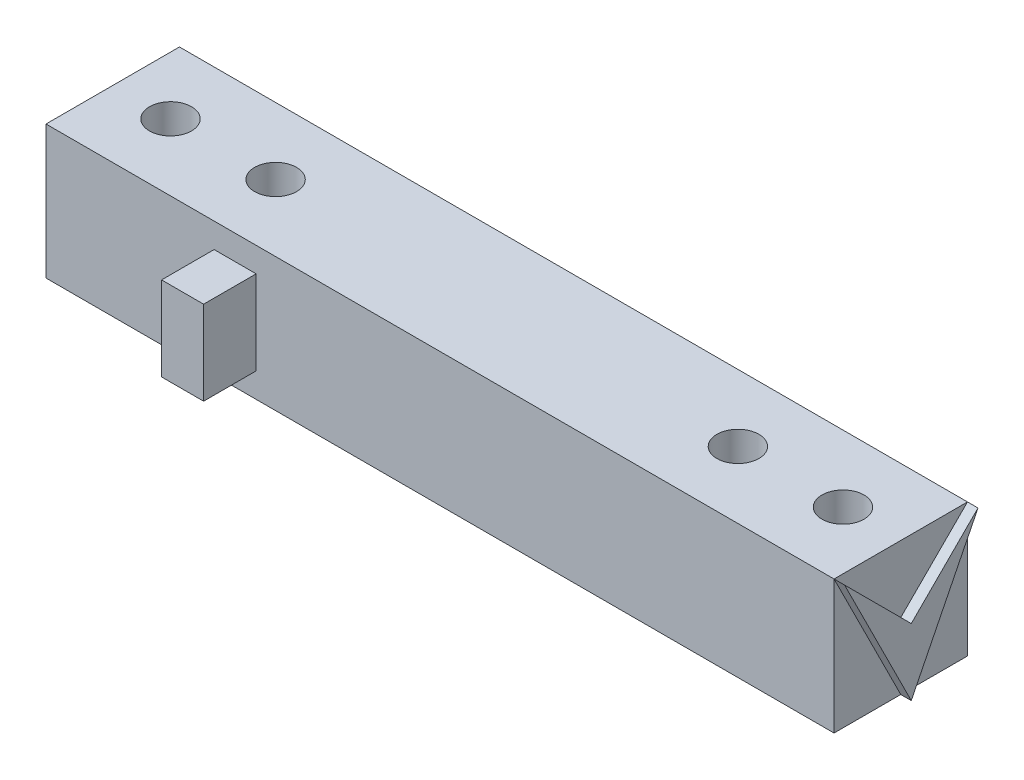
SolidWorks part; units mm, degrees
material "AISI 1020"
ref_plane "Front Plane" through (0, 0, 0) normal (0, 0, 1) x (1, 0, 0)
ref_plane "Top Plane" through (0, 0, 0) normal (0, 1, 0) x (1, 0, 0)
ref_plane "Right Plane" through (0, 0, 0) normal (1, 0, 0) x (0, 0, -1)
sketch "Sketch1" plane through (0, 0, 0) normal (0, 1, 0) x (1, 0, 0)
  line L1 (0, 0) -> (75, 0)
  line L2 (0, 0) -> (0, 12.7)
  line L3 (0, 12.7) -> (75, 12.7)
  line L4 (75, 0) -> (75, 12.7)
  dimension "D1" = 12.7
  dimension "D2" = 75
extrude "Boss-Extrude1" add sketch "Sketch1" along normal blind 12.7
sketch "Sketch2" plane through (0, 12.7, 0) normal (0, 1, 0) x (1, 0, 0)
  line L0 (0, 6.35) -> (75, 6.35) construction
  line L1 (0, 12.7) -> (0, 0) construction
  line L2 (75, 0) -> (75, 12.7) construction
  line L3 (37.5, 12.7) -> (37.5, 0) construction
  line L4 (75, 12.7) -> (0, 12.7) construction
  line L5 (0, 0) -> (75, 0) construction
  line L6 (37.5, 6.35) -> (15.5, 6.35) construction
  line L7 (15.5, 6.35) -> (5.5, 6.35) construction
  point P15 (59.5, 6.35)
  point P16 (5.5, 6.35)
  point P17 (15.5, 6.35)
  point P18 (69.5, 6.35)
  dimension "D1" = 22
  dimension "D2" = 10
hole_wizard "Ø4.0mm Dowel Hole1" positions "Sketch2" profile "Sketch3" hole size "Ø4.0" standard "ANSI Metric"
sketch "Sketch3" plane through (69.5, 12.7, -6.35) normal (1, 0, 0) x (0, 0, 1)
  line L0 (0, 0) -> (0, 118.8308)
  line L1 (0, 118.8308) -> (2, 117.6291)
  line L2 (2, 117.6291) -> (2, 0)
  line L5 (2, 0) -> (0, 0)
  line L10 (0, 118.8308) -> (-2, 117.6291) construction
  line L11 (0, -6.35) -> (0, 107.95) construction
  dimension "Hole Dia." = 4
  dimension "Hole Depth" = 117.6291
  dimension "Drill Angle" = 118
sketch "Sketch4" plane through (0, 0, 0) normal (0, 0, 1) x (1, 0, 0)
  line L0 (0, 6.35) -> (18, 6.35) construction
  line L1 (0, 12.7) -> (0, 0) construction
  line L3 (20, 2.35) -> (16, 2.35)
  line L4 (20, 2.35) -> (20, 10.35)
  line L5 (20, 10.35) -> (16, 10.35)
  line L6 (16, 2.35) -> (16, 10.35)
  line L7 (20, 2.35) -> (16, 10.35) construction
  line L8 (20, 10.35) -> (16, 2.35) construction
  dimension "D1" = 18
  dimension "D2" = 8
  dimension "D3" = 4
extrude "Boss-Extrude2" add sketch "Sketch4" along normal blind 5
sketch "Sketch6" plane through (75, 0, 0) normal (1, 0, 0) x (0, 0, -1)
  line L0 (6.35, 12.7) -> (6.35, 0) construction
  line L1 (0, 12.7) -> (12.7, 12.7) construction
  line L2 (0, 0) -> (12.7, 0) construction
  line L3 (6.35, 0) -> (12.7, 12.7)
  line L4 (12.7, 12.7) -> (6.35, 6.35)
  line L5 (6.35, 6.35) -> (0, 12.7)
  line L6 (0, 12.7) -> (6.35, 0)
extrude "Boss-Extrude3" add sketch "Sketch6" along normal blind 1
